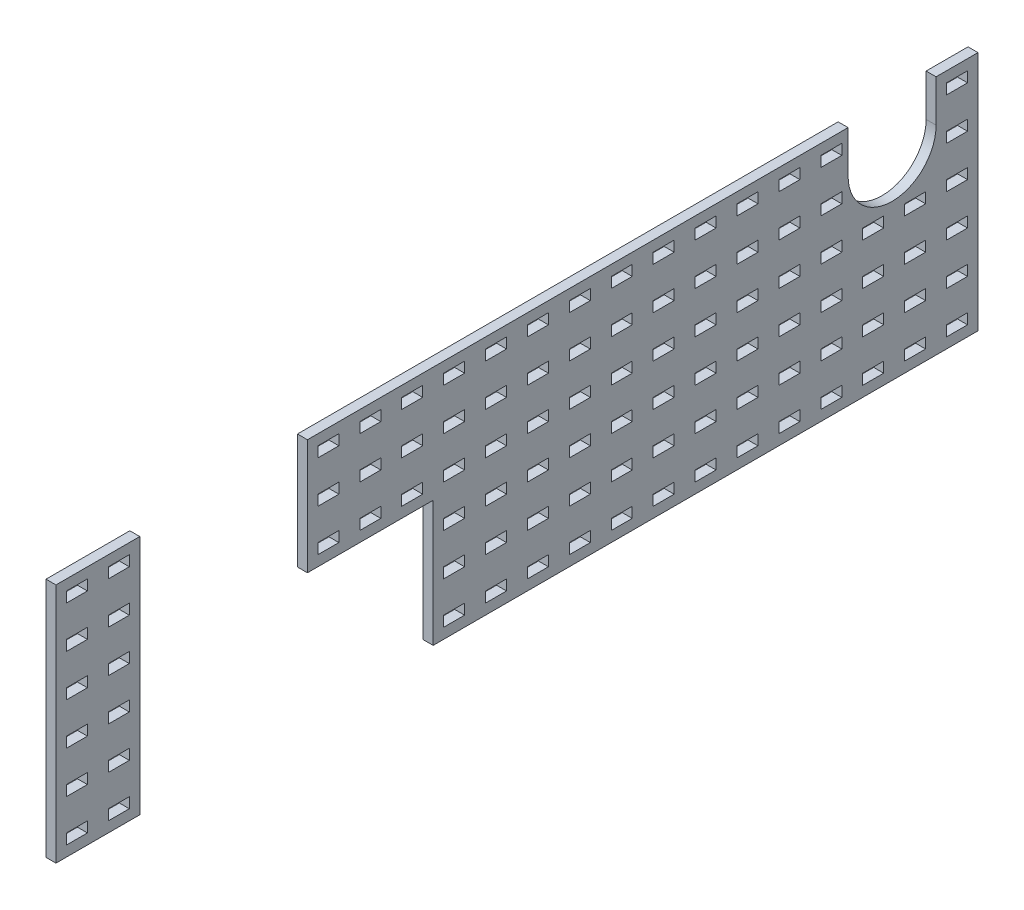
SolidWorks part; units mm, degrees
ref_plane "Front Plane" through (0, 0, 0) normal (0, 0, 1) x (1, 0, 0)
ref_plane "Top Plane" through (0, 0, 0) normal (0, 1, 0) x (1, 0, 0)
ref_plane "Right Plane" through (0, 0, 0) normal (1, 0, 0) x (0, 0, -1)
sketch "Sketch1" plane through (0, 0, 0) normal (1, 0, 0) x (0, 0, -1)
  line L1 (-279.4, -73.025) -> (279.4, -73.025)
  line L2 (-279.4, -73.025) -> (-279.4, 73.025)
  line L3 (-279.4, 73.025) -> (279.4, 73.025)
  line L4 (279.4, -73.025) -> (279.4, 73.025)
  line L5 (-279.4, -73.025) -> (279.4, 73.025) construction
  line L6 (-279.4, 73.025) -> (279.4, -73.025) construction
  point P0 (0, 0)
  dimension "D1" = 558.8
  dimension "D2" = 146.05
extrude "Boss-Extrude1" add sketch "Sketch1" along normal mid plane 6.0452
sketch "Sketch2" plane through (3.0226, 0, 0) normal (1, 0, 0) x (0, 0, -1)
  line L0 (-279.4, -73.025) -> (279.4, -73.025) construction
  line L1 (260.35, -60.325) -> (273.05, -60.325)
  line L2 (260.35, -60.325) -> (260.35, -66.675)
  line L3 (260.35, -66.675) -> (273.05, -66.675)
  line L4 (273.05, -60.325) -> (273.05, -66.675)
  line L5 (260.35, -60.325) -> (273.05, -66.675) construction
  line L6 (260.35, -66.675) -> (273.05, -60.325) construction
  line L7 (279.4, -73.025) -> (279.4, 73.025) construction
  line L8 (234.95, -66.675) -> (247.65, -66.675)
  line L9 (234.95, -60.325) -> (234.95, -66.675)
  line L10 (234.95, -60.325) -> (247.65, -60.325)
  line L11 (247.65, -60.325) -> (247.65, -66.675)
  line L12 (209.55, -66.675) -> (222.25, -66.675)
  line L13 (209.55, -60.325) -> (209.55, -66.675)
  line L14 (209.55, -60.325) -> (222.25, -60.325)
  line L15 (222.25, -60.325) -> (222.25, -66.675)
  line L16 (184.15, -66.675) -> (196.85, -66.675)
  line L17 (184.15, -60.325) -> (184.15, -66.675)
  line L18 (184.15, -60.325) -> (196.85, -60.325)
  line L19 (196.85, -60.325) -> (196.85, -66.675)
  line L20 (158.75, -66.675) -> (171.45, -66.675)
  line L21 (158.75, -60.325) -> (158.75, -66.675)
  line L22 (158.75, -60.325) -> (171.45, -60.325)
  line L23 (171.45, -60.325) -> (171.45, -66.675)
  line L24 (133.35, -66.675) -> (146.05, -66.675)
  line L25 (133.35, -60.325) -> (133.35, -66.675)
  line L26 (133.35, -60.325) -> (146.05, -60.325)
  line L27 (146.05, -60.325) -> (146.05, -66.675)
  line L28 (107.95, -66.675) -> (120.65, -66.675)
  line L29 (107.95, -60.325) -> (107.95, -66.675)
  line L30 (107.95, -60.325) -> (120.65, -60.325)
  line L31 (120.65, -60.325) -> (120.65, -66.675)
  line L32 (82.55, -66.675) -> (95.25, -66.675)
  line L33 (82.55, -60.325) -> (82.55, -66.675)
  line L34 (82.55, -60.325) -> (95.25, -60.325)
  line L35 (95.25, -60.325) -> (95.25, -66.675)
  line L36 (57.15, -66.675) -> (69.85, -66.675)
  line L37 (57.15, -60.325) -> (57.15, -66.675)
  line L38 (57.15, -60.325) -> (69.85, -60.325)
  line L39 (69.85, -60.325) -> (69.85, -66.675)
  line L40 (31.75, -66.675) -> (44.45, -66.675)
  line L41 (31.75, -60.325) -> (31.75, -66.675)
  line L42 (31.75, -60.325) -> (44.45, -60.325)
  line L43 (44.45, -60.325) -> (44.45, -66.675)
  line L44 (6.35, -66.675) -> (19.05, -66.675)
  line L45 (6.35, -60.325) -> (6.35, -66.675)
  line L46 (6.35, -60.325) -> (19.05, -60.325)
  line L47 (19.05, -60.325) -> (19.05, -66.675)
  line L48 (-19.05, -66.675) -> (-6.35, -66.675)
  line L49 (-19.05, -60.325) -> (-19.05, -66.675)
  line L50 (-19.05, -60.325) -> (-6.35, -60.325)
  line L51 (-6.35, -60.325) -> (-6.35, -66.675)
  line L52 (-44.45, -66.675) -> (-31.75, -66.675)
  line L53 (-44.45, -60.325) -> (-44.45, -66.675)
  line L54 (-44.45, -60.325) -> (-31.75, -60.325)
  line L55 (-31.75, -60.325) -> (-31.75, -66.675)
  line L56 (-69.85, -66.675) -> (-57.15, -66.675)
  line L57 (-69.85, -60.325) -> (-69.85, -66.675)
  line L58 (-69.85, -60.325) -> (-57.15, -60.325)
  line L59 (-57.15, -60.325) -> (-57.15, -66.675)
  line L60 (-95.25, -66.675) -> (-82.55, -66.675)
  line L61 (-95.25, -60.325) -> (-95.25, -66.675)
  line L62 (-95.25, -60.325) -> (-82.55, -60.325)
  line L63 (-82.55, -60.325) -> (-82.55, -66.675)
  line L64 (-120.65, -66.675) -> (-107.95, -66.675)
  line L65 (-120.65, -60.325) -> (-120.65, -66.675)
  line L66 (-120.65, -60.325) -> (-107.95, -60.325)
  line L67 (-107.95, -60.325) -> (-107.95, -66.675)
  line L68 (-146.05, -66.675) -> (-133.35, -66.675)
  line L69 (-146.05, -60.325) -> (-146.05, -66.675)
  line L70 (-146.05, -60.325) -> (-133.35, -60.325)
  line L71 (-133.35, -60.325) -> (-133.35, -66.675)
  line L72 (-171.45, -66.675) -> (-158.75, -66.675)
  line L73 (-171.45, -60.325) -> (-171.45, -66.675)
  line L74 (-171.45, -60.325) -> (-158.75, -60.325)
  line L75 (-158.75, -60.325) -> (-158.75, -66.675)
  line L76 (-196.85, -66.675) -> (-184.15, -66.675)
  line L77 (-196.85, -60.325) -> (-196.85, -66.675)
  line L78 (-196.85, -60.325) -> (-184.15, -60.325)
  line L79 (-184.15, -60.325) -> (-184.15, -66.675)
  line L80 (-222.25, -66.675) -> (-209.55, -66.675)
  line L81 (-222.25, -60.325) -> (-222.25, -66.675)
  line L82 (-222.25, -60.325) -> (-209.55, -60.325)
  line L83 (-209.55, -60.325) -> (-209.55, -66.675)
  line L84 (-247.65, -66.675) -> (-234.95, -66.675)
  line L85 (-247.65, -60.325) -> (-247.65, -66.675)
  line L86 (-247.65, -60.325) -> (-234.95, -60.325)
  line L87 (-234.95, -60.325) -> (-234.95, -66.675)
  line L88 (-273.05, -66.675) -> (-260.35, -66.675)
  line L89 (-273.05, -60.325) -> (-273.05, -66.675)
  line L90 (-273.05, -60.325) -> (-260.35, -60.325)
  line L91 (-260.35, -60.325) -> (-260.35, -66.675)
  line L92 (234.95, -41.275) -> (247.65, -41.275)
  line L93 (234.95, -34.925) -> (234.95, -41.275)
  line L94 (234.95, -34.925) -> (247.65, -34.925)
  line L95 (247.65, -34.925) -> (247.65, -41.275)
  line L96 (209.55, -41.275) -> (222.25, -41.275)
  line L97 (209.55, -34.925) -> (209.55, -41.275)
  line L98 (209.55, -34.925) -> (222.25, -34.925)
  line L99 (222.25, -34.925) -> (222.25, -41.275)
  line L100 (184.15, -41.275) -> (196.85, -41.275)
  line L101 (184.15, -34.925) -> (184.15, -41.275)
  line L102 (184.15, -34.925) -> (196.85, -34.925)
  line L103 (196.85, -34.925) -> (196.85, -41.275)
  line L104 (158.75, -41.275) -> (171.45, -41.275)
  line L105 (158.75, -34.925) -> (158.75, -41.275)
  line L106 (158.75, -34.925) -> (171.45, -34.925)
  line L107 (171.45, -34.925) -> (171.45, -41.275)
  line L108 (133.35, -41.275) -> (146.05, -41.275)
  line L109 (133.35, -34.925) -> (133.35, -41.275)
  line L110 (133.35, -34.925) -> (146.05, -34.925)
  line L111 (146.05, -34.925) -> (146.05, -41.275)
  line L112 (107.95, -41.275) -> (120.65, -41.275)
  line L113 (107.95, -34.925) -> (107.95, -41.275)
  line L114 (107.95, -34.925) -> (120.65, -34.925)
  line L115 (120.65, -34.925) -> (120.65, -41.275)
  line L116 (82.55, -41.275) -> (95.25, -41.275)
  line L117 (82.55, -34.925) -> (82.55, -41.275)
  line L118 (82.55, -34.925) -> (95.25, -34.925)
  line L119 (95.25, -34.925) -> (95.25, -41.275)
  line L120 (57.15, -41.275) -> (69.85, -41.275)
  line L121 (57.15, -34.925) -> (57.15, -41.275)
  line L122 (57.15, -34.925) -> (69.85, -34.925)
  line L123 (69.85, -34.925) -> (69.85, -41.275)
  line L124 (31.75, -41.275) -> (44.45, -41.275)
  line L125 (31.75, -34.925) -> (31.75, -41.275)
  line L126 (31.75, -34.925) -> (44.45, -34.925)
  line L127 (44.45, -34.925) -> (44.45, -41.275)
  line L128 (6.35, -41.275) -> (19.05, -41.275)
  line L129 (6.35, -34.925) -> (6.35, -41.275)
  line L130 (6.35, -34.925) -> (19.05, -34.925)
  line L131 (19.05, -34.925) -> (19.05, -41.275)
  line L132 (-19.05, -41.275) -> (-6.35, -41.275)
  line L133 (-19.05, -34.925) -> (-19.05, -41.275)
  line L134 (-19.05, -34.925) -> (-6.35, -34.925)
  line L135 (-6.35, -34.925) -> (-6.35, -41.275)
  line L136 (-44.45, -41.275) -> (-31.75, -41.275)
  line L137 (-44.45, -34.925) -> (-44.45, -41.275)
  line L138 (-44.45, -34.925) -> (-31.75, -34.925)
  line L139 (-31.75, -34.925) -> (-31.75, -41.275)
  line L140 (-69.85, -41.275) -> (-57.15, -41.275)
  line L141 (-69.85, -34.925) -> (-69.85, -41.275)
  line L142 (-69.85, -34.925) -> (-57.15, -34.925)
  line L143 (-57.15, -34.925) -> (-57.15, -41.275)
  line L144 (-95.25, -41.275) -> (-82.55, -41.275)
  line L145 (-95.25, -34.925) -> (-95.25, -41.275)
  line L146 (-95.25, -34.925) -> (-82.55, -34.925)
  line L147 (-82.55, -34.925) -> (-82.55, -41.275)
  line L148 (-120.65, -41.275) -> (-107.95, -41.275)
  line L149 (-120.65, -34.925) -> (-120.65, -41.275)
  line L150 (-120.65, -34.925) -> (-107.95, -34.925)
  line L151 (-107.95, -34.925) -> (-107.95, -41.275)
  line L152 (-146.05, -41.275) -> (-133.35, -41.275)
  line L153 (-146.05, -34.925) -> (-146.05, -41.275)
  line L154 (-146.05, -34.925) -> (-133.35, -34.925)
  line L155 (-133.35, -34.925) -> (-133.35, -41.275)
  line L156 (-171.45, -41.275) -> (-158.75, -41.275)
  line L157 (-171.45, -34.925) -> (-171.45, -41.275)
  line L158 (-171.45, -34.925) -> (-158.75, -34.925)
  line L159 (-158.75, -34.925) -> (-158.75, -41.275)
  line L160 (-196.85, -41.275) -> (-184.15, -41.275)
  line L161 (-196.85, -34.925) -> (-196.85, -41.275)
  line L162 (-196.85, -34.925) -> (-184.15, -34.925)
  line L163 (-184.15, -34.925) -> (-184.15, -41.275)
  line L164 (-222.25, -41.275) -> (-209.55, -41.275)
  line L165 (-222.25, -34.925) -> (-222.25, -41.275)
  line L166 (-222.25, -34.925) -> (-209.55, -34.925)
  line L167 (-209.55, -34.925) -> (-209.55, -41.275)
  line L168 (-247.65, -41.275) -> (-234.95, -41.275)
  line L169 (-247.65, -34.925) -> (-247.65, -41.275)
  line L170 (-247.65, -34.925) -> (-234.95, -34.925)
  line L171 (-234.95, -34.925) -> (-234.95, -41.275)
  line L172 (-273.05, -41.275) -> (-260.35, -41.275)
  line L173 (-273.05, -34.925) -> (-273.05, -41.275)
  line L174 (-273.05, -34.925) -> (-260.35, -34.925)
  line L175 (-260.35, -34.925) -> (-260.35, -41.275)
  line L176 (234.95, -15.875) -> (247.65, -15.875)
  line L177 (234.95, -9.525) -> (234.95, -15.875)
  line L178 (234.95, -9.525) -> (247.65, -9.525)
  line L179 (247.65, -9.525) -> (247.65, -15.875)
  line L180 (209.55, -15.875) -> (222.25, -15.875)
  line L181 (209.55, -9.525) -> (209.55, -15.875)
  line L182 (209.55, -9.525) -> (222.25, -9.525)
  line L183 (222.25, -9.525) -> (222.25, -15.875)
  line L184 (184.15, -15.875) -> (196.85, -15.875)
  line L185 (184.15, -9.525) -> (184.15, -15.875)
  line L186 (184.15, -9.525) -> (196.85, -9.525)
  line L187 (196.85, -9.525) -> (196.85, -15.875)
  line L188 (158.75, -15.875) -> (171.45, -15.875)
  line L189 (158.75, -9.525) -> (158.75, -15.875)
  line L190 (158.75, -9.525) -> (171.45, -9.525)
  line L191 (171.45, -9.525) -> (171.45, -15.875)
  line L192 (133.35, -15.875) -> (146.05, -15.875)
  line L193 (133.35, -9.525) -> (133.35, -15.875)
  line L194 (133.35, -9.525) -> (146.05, -9.525)
  line L195 (146.05, -9.525) -> (146.05, -15.875)
  line L196 (107.95, -15.875) -> (120.65, -15.875)
  line L197 (107.95, -9.525) -> (107.95, -15.875)
  line L198 (107.95, -9.525) -> (120.65, -9.525)
  line L199 (120.65, -9.525) -> (120.65, -15.875)
  line L200 (82.55, -15.875) -> (95.25, -15.875)
  line L201 (82.55, -9.525) -> (82.55, -15.875)
  line L202 (82.55, -9.525) -> (95.25, -9.525)
  line L203 (95.25, -9.525) -> (95.25, -15.875)
  line L204 (57.15, -15.875) -> (69.85, -15.875)
  line L205 (57.15, -9.525) -> (57.15, -15.875)
  line L206 (57.15, -9.525) -> (69.85, -9.525)
  line L207 (69.85, -9.525) -> (69.85, -15.875)
  line L208 (31.75, -15.875) -> (44.45, -15.875)
  line L209 (31.75, -9.525) -> (31.75, -15.875)
  line L210 (31.75, -9.525) -> (44.45, -9.525)
  line L211 (44.45, -9.525) -> (44.45, -15.875)
  line L212 (6.35, -15.875) -> (19.05, -15.875)
  line L213 (6.35, -9.525) -> (6.35, -15.875)
  line L214 (6.35, -9.525) -> (19.05, -9.525)
  line L215 (19.05, -9.525) -> (19.05, -15.875)
  line L216 (-19.05, -15.875) -> (-6.35, -15.875)
  line L217 (-19.05, -9.525) -> (-19.05, -15.875)
  line L218 (-19.05, -9.525) -> (-6.35, -9.525)
  line L219 (-6.35, -9.525) -> (-6.35, -15.875)
  line L220 (-44.45, -15.875) -> (-31.75, -15.875)
  line L221 (-44.45, -9.525) -> (-44.45, -15.875)
  line L222 (-44.45, -9.525) -> (-31.75, -9.525)
  line L223 (-31.75, -9.525) -> (-31.75, -15.875)
  line L224 (-69.85, -15.875) -> (-57.15, -15.875)
  line L225 (-69.85, -9.525) -> (-69.85, -15.875)
  line L226 (-69.85, -9.525) -> (-57.15, -9.525)
  line L227 (-57.15, -9.525) -> (-57.15, -15.875)
  line L228 (-95.25, -15.875) -> (-82.55, -15.875)
  line L229 (-95.25, -9.525) -> (-95.25, -15.875)
  line L230 (-95.25, -9.525) -> (-82.55, -9.525)
  line L231 (-82.55, -9.525) -> (-82.55, -15.875)
  line L232 (-120.65, -15.875) -> (-107.95, -15.875)
  line L233 (-120.65, -9.525) -> (-120.65, -15.875)
  line L234 (-120.65, -9.525) -> (-107.95, -9.525)
  line L235 (-107.95, -9.525) -> (-107.95, -15.875)
  line L236 (-146.05, -15.875) -> (-133.35, -15.875)
  line L237 (-146.05, -9.525) -> (-146.05, -15.875)
  line L238 (-146.05, -9.525) -> (-133.35, -9.525)
  line L239 (-133.35, -9.525) -> (-133.35, -15.875)
  line L240 (-171.45, -15.875) -> (-158.75, -15.875)
  line L241 (-171.45, -9.525) -> (-171.45, -15.875)
  line L242 (-171.45, -9.525) -> (-158.75, -9.525)
  line L243 (-158.75, -9.525) -> (-158.75, -15.875)
  line L244 (-196.85, -15.875) -> (-184.15, -15.875)
  line L245 (-196.85, -9.525) -> (-196.85, -15.875)
  line L246 (-196.85, -9.525) -> (-184.15, -9.525)
  line L247 (-184.15, -9.525) -> (-184.15, -15.875)
  line L248 (-222.25, -15.875) -> (-209.55, -15.875)
  line L249 (-222.25, -9.525) -> (-222.25, -15.875)
  line L250 (-222.25, -9.525) -> (-209.55, -9.525)
  line L251 (-209.55, -9.525) -> (-209.55, -15.875)
  line L252 (-247.65, -15.875) -> (-234.95, -15.875)
  line L253 (-247.65, -9.525) -> (-247.65, -15.875)
  line L254 (-247.65, -9.525) -> (-234.95, -9.525)
  line L255 (-234.95, -9.525) -> (-234.95, -15.875)
  line L256 (-273.05, -15.875) -> (-260.35, -15.875)
  line L257 (-273.05, -9.525) -> (-273.05, -15.875)
  line L258 (-273.05, -9.525) -> (-260.35, -9.525)
  line L259 (-260.35, -9.525) -> (-260.35, -15.875)
  line L260 (234.95, 9.525) -> (247.65, 9.525)
  line L261 (234.95, 15.875) -> (234.95, 9.525)
  line L262 (234.95, 15.875) -> (247.65, 15.875)
  line L263 (247.65, 15.875) -> (247.65, 9.525)
  line L264 (209.55, 9.525) -> (222.25, 9.525)
  line L265 (209.55, 15.875) -> (209.55, 9.525)
  line L266 (209.55, 15.875) -> (222.25, 15.875)
  line L267 (222.25, 15.875) -> (222.25, 9.525)
  line L268 (184.15, 9.525) -> (196.85, 9.525)
  line L269 (184.15, 15.875) -> (184.15, 9.525)
  line L270 (184.15, 15.875) -> (196.85, 15.875)
  line L271 (196.85, 15.875) -> (196.85, 9.525)
  line L272 (158.75, 9.525) -> (171.45, 9.525)
  line L273 (158.75, 15.875) -> (158.75, 9.525)
  line L274 (158.75, 15.875) -> (171.45, 15.875)
  line L275 (171.45, 15.875) -> (171.45, 9.525)
  line L276 (133.35, 9.525) -> (146.05, 9.525)
  line L277 (133.35, 15.875) -> (133.35, 9.525)
  line L278 (133.35, 15.875) -> (146.05, 15.875)
  line L279 (146.05, 15.875) -> (146.05, 9.525)
  line L280 (107.95, 9.525) -> (120.65, 9.525)
  line L281 (107.95, 15.875) -> (107.95, 9.525)
  line L282 (107.95, 15.875) -> (120.65, 15.875)
  line L283 (120.65, 15.875) -> (120.65, 9.525)
  line L284 (82.55, 9.525) -> (95.25, 9.525)
  line L285 (82.55, 15.875) -> (82.55, 9.525)
  line L286 (82.55, 15.875) -> (95.25, 15.875)
  line L287 (95.25, 15.875) -> (95.25, 9.525)
  line L288 (57.15, 9.525) -> (69.85, 9.525)
  line L289 (57.15, 15.875) -> (57.15, 9.525)
  line L290 (57.15, 15.875) -> (69.85, 15.875)
  line L291 (69.85, 15.875) -> (69.85, 9.525)
  line L292 (31.75, 9.525) -> (44.45, 9.525)
  line L293 (31.75, 15.875) -> (31.75, 9.525)
  line L294 (31.75, 15.875) -> (44.45, 15.875)
  line L295 (44.45, 15.875) -> (44.45, 9.525)
  line L296 (6.35, 9.525) -> (19.05, 9.525)
  line L297 (6.35, 15.875) -> (6.35, 9.525)
  line L298 (6.35, 15.875) -> (19.05, 15.875)
  line L299 (19.05, 15.875) -> (19.05, 9.525)
  line L300 (-19.05, 9.525) -> (-6.35, 9.525)
  line L301 (-19.05, 15.875) -> (-19.05, 9.525)
  line L302 (-19.05, 15.875) -> (-6.35, 15.875)
  line L303 (-6.35, 15.875) -> (-6.35, 9.525)
  line L304 (-44.45, 9.525) -> (-31.75, 9.525)
  line L305 (-44.45, 15.875) -> (-44.45, 9.525)
  line L306 (-44.45, 15.875) -> (-31.75, 15.875)
  line L307 (-31.75, 15.875) -> (-31.75, 9.525)
  line L308 (-69.85, 9.525) -> (-57.15, 9.525)
  line L309 (-69.85, 15.875) -> (-69.85, 9.525)
  line L310 (-69.85, 15.875) -> (-57.15, 15.875)
  line L311 (-57.15, 15.875) -> (-57.15, 9.525)
  line L312 (-95.25, 9.525) -> (-82.55, 9.525)
  line L313 (-95.25, 15.875) -> (-95.25, 9.525)
  line L314 (-95.25, 15.875) -> (-82.55, 15.875)
  line L315 (-82.55, 15.875) -> (-82.55, 9.525)
  line L316 (-120.65, 9.525) -> (-107.95, 9.525)
  line L317 (-120.65, 15.875) -> (-120.65, 9.525)
  line L318 (-120.65, 15.875) -> (-107.95, 15.875)
  line L319 (-107.95, 15.875) -> (-107.95, 9.525)
  line L320 (-146.05, 9.525) -> (-133.35, 9.525)
  line L321 (-146.05, 15.875) -> (-146.05, 9.525)
  line L322 (-146.05, 15.875) -> (-133.35, 15.875)
  line L323 (-133.35, 15.875) -> (-133.35, 9.525)
  line L324 (-171.45, 9.525) -> (-158.75, 9.525)
  line L325 (-171.45, 15.875) -> (-171.45, 9.525)
  line L326 (-171.45, 15.875) -> (-158.75, 15.875)
  line L327 (-158.75, 15.875) -> (-158.75, 9.525)
  line L328 (-196.85, 9.525) -> (-184.15, 9.525)
  line L329 (-196.85, 15.875) -> (-196.85, 9.525)
  line L330 (-196.85, 15.875) -> (-184.15, 15.875)
  line L331 (-184.15, 15.875) -> (-184.15, 9.525)
  line L332 (-222.25, 9.525) -> (-209.55, 9.525)
  line L333 (-222.25, 15.875) -> (-222.25, 9.525)
  line L334 (-222.25, 15.875) -> (-209.55, 15.875)
  line L335 (-209.55, 15.875) -> (-209.55, 9.525)
  line L336 (-247.65, 9.525) -> (-234.95, 9.525)
  line L337 (-247.65, 15.875) -> (-247.65, 9.525)
  line L338 (-247.65, 15.875) -> (-234.95, 15.875)
  line L339 (-234.95, 15.875) -> (-234.95, 9.525)
  line L340 (-273.05, 9.525) -> (-260.35, 9.525)
  line L341 (-273.05, 15.875) -> (-273.05, 9.525)
  line L342 (-273.05, 15.875) -> (-260.35, 15.875)
  line L343 (-260.35, 15.875) -> (-260.35, 9.525)
  line L344 (234.95, 34.925) -> (247.65, 34.925)
  line L345 (234.95, 41.275) -> (234.95, 34.925)
  line L346 (234.95, 41.275) -> (247.65, 41.275)
  line L347 (247.65, 41.275) -> (247.65, 34.925)
  line L348 (209.55, 34.925) -> (222.25, 34.925)
  line L349 (209.55, 41.275) -> (209.55, 34.925)
  line L350 (209.55, 41.275) -> (222.25, 41.275)
  line L351 (222.25, 41.275) -> (222.25, 34.925)
  line L352 (184.15, 34.925) -> (196.85, 34.925)
  line L353 (184.15, 41.275) -> (184.15, 34.925)
  line L354 (184.15, 41.275) -> (196.85, 41.275)
  line L355 (196.85, 41.275) -> (196.85, 34.925)
  line L356 (158.75, 34.925) -> (171.45, 34.925)
  line L357 (158.75, 41.275) -> (158.75, 34.925)
  line L358 (158.75, 41.275) -> (171.45, 41.275)
  line L359 (171.45, 41.275) -> (171.45, 34.925)
  line L360 (133.35, 34.925) -> (146.05, 34.925)
  line L361 (133.35, 41.275) -> (133.35, 34.925)
  line L362 (133.35, 41.275) -> (146.05, 41.275)
  line L363 (146.05, 41.275) -> (146.05, 34.925)
  line L364 (107.95, 34.925) -> (120.65, 34.925)
  line L365 (107.95, 41.275) -> (107.95, 34.925)
  line L366 (107.95, 41.275) -> (120.65, 41.275)
  line L367 (120.65, 41.275) -> (120.65, 34.925)
  line L368 (82.55, 34.925) -> (95.25, 34.925)
  line L369 (82.55, 41.275) -> (82.55, 34.925)
  line L370 (82.55, 41.275) -> (95.25, 41.275)
  line L371 (95.25, 41.275) -> (95.25, 34.925)
  line L372 (57.15, 34.925) -> (69.85, 34.925)
  line L373 (57.15, 41.275) -> (57.15, 34.925)
  line L374 (57.15, 41.275) -> (69.85, 41.275)
  line L375 (69.85, 41.275) -> (69.85, 34.925)
  line L376 (31.75, 34.925) -> (44.45, 34.925)
  line L377 (31.75, 41.275) -> (31.75, 34.925)
  line L378 (31.75, 41.275) -> (44.45, 41.275)
  line L379 (44.45, 41.275) -> (44.45, 34.925)
  line L380 (6.35, 34.925) -> (19.05, 34.925)
  line L381 (6.35, 41.275) -> (6.35, 34.925)
  line L382 (6.35, 41.275) -> (19.05, 41.275)
  line L383 (19.05, 41.275) -> (19.05, 34.925)
  line L384 (-19.05, 34.925) -> (-6.35, 34.925)
  line L385 (-19.05, 41.275) -> (-19.05, 34.925)
  line L386 (-19.05, 41.275) -> (-6.35, 41.275)
  line L387 (-6.35, 41.275) -> (-6.35, 34.925)
  line L388 (-44.45, 34.925) -> (-31.75, 34.925)
  line L389 (-44.45, 41.275) -> (-44.45, 34.925)
  line L390 (-44.45, 41.275) -> (-31.75, 41.275)
  line L391 (-31.75, 41.275) -> (-31.75, 34.925)
  line L392 (-69.85, 34.925) -> (-57.15, 34.925)
  line L393 (-69.85, 41.275) -> (-69.85, 34.925)
  line L394 (-69.85, 41.275) -> (-57.15, 41.275)
  line L395 (-57.15, 41.275) -> (-57.15, 34.925)
  line L396 (-95.25, 34.925) -> (-82.55, 34.925)
  line L397 (-95.25, 41.275) -> (-95.25, 34.925)
  line L398 (-95.25, 41.275) -> (-82.55, 41.275)
  line L399 (-82.55, 41.275) -> (-82.55, 34.925)
  line L400 (-120.65, 34.925) -> (-107.95, 34.925)
  line L401 (-120.65, 41.275) -> (-120.65, 34.925)
  line L402 (-120.65, 41.275) -> (-107.95, 41.275)
  line L403 (-107.95, 41.275) -> (-107.95, 34.925)
  line L404 (-146.05, 34.925) -> (-133.35, 34.925)
  line L405 (-146.05, 41.275) -> (-146.05, 34.925)
  line L406 (-146.05, 41.275) -> (-133.35, 41.275)
  line L407 (-133.35, 41.275) -> (-133.35, 34.925)
  line L408 (-171.45, 34.925) -> (-158.75, 34.925)
  line L409 (-171.45, 41.275) -> (-171.45, 34.925)
  line L410 (-171.45, 41.275) -> (-158.75, 41.275)
  line L411 (-158.75, 41.275) -> (-158.75, 34.925)
  line L412 (-196.85, 34.925) -> (-184.15, 34.925)
  line L413 (-196.85, 41.275) -> (-196.85, 34.925)
  line L414 (-196.85, 41.275) -> (-184.15, 41.275)
  line L415 (-184.15, 41.275) -> (-184.15, 34.925)
  line L416 (-222.25, 34.925) -> (-209.55, 34.925)
  line L417 (-222.25, 41.275) -> (-222.25, 34.925)
  line L418 (-222.25, 41.275) -> (-209.55, 41.275)
  line L419 (-209.55, 41.275) -> (-209.55, 34.925)
  line L420 (-247.65, 34.925) -> (-234.95, 34.925)
  line L421 (-247.65, 41.275) -> (-247.65, 34.925)
  line L422 (-247.65, 41.275) -> (-234.95, 41.275)
  line L423 (-234.95, 41.275) -> (-234.95, 34.925)
  line L424 (-273.05, 34.925) -> (-260.35, 34.925)
  line L425 (-273.05, 41.275) -> (-273.05, 34.925)
  line L426 (-273.05, 41.275) -> (-260.35, 41.275)
  line L427 (-260.35, 41.275) -> (-260.35, 34.925)
  line L428 (234.95, 60.325) -> (247.65, 60.325)
  line L429 (234.95, 66.675) -> (234.95, 60.325)
  line L430 (234.95, 66.675) -> (247.65, 66.675)
  line L431 (247.65, 66.675) -> (247.65, 60.325)
  line L432 (209.55, 60.325) -> (222.25, 60.325)
  line L433 (209.55, 66.675) -> (209.55, 60.325)
  line L434 (209.55, 66.675) -> (222.25, 66.675)
  line L435 (222.25, 66.675) -> (222.25, 60.325)
  line L436 (184.15, 60.325) -> (196.85, 60.325)
  line L437 (184.15, 66.675) -> (184.15, 60.325)
  line L438 (184.15, 66.675) -> (196.85, 66.675)
  line L439 (196.85, 66.675) -> (196.85, 60.325)
  line L440 (158.75, 60.325) -> (171.45, 60.325)
  line L441 (158.75, 66.675) -> (158.75, 60.325)
  line L442 (158.75, 66.675) -> (171.45, 66.675)
  line L443 (171.45, 66.675) -> (171.45, 60.325)
  line L444 (133.35, 60.325) -> (146.05, 60.325)
  line L445 (133.35, 66.675) -> (133.35, 60.325)
  line L446 (133.35, 66.675) -> (146.05, 66.675)
  line L447 (146.05, 66.675) -> (146.05, 60.325)
  line L448 (107.95, 60.325) -> (120.65, 60.325)
  line L449 (107.95, 66.675) -> (107.95, 60.325)
  line L450 (107.95, 66.675) -> (120.65, 66.675)
  line L451 (120.65, 66.675) -> (120.65, 60.325)
  line L452 (82.55, 60.325) -> (95.25, 60.325)
  line L453 (82.55, 66.675) -> (82.55, 60.325)
  line L454 (82.55, 66.675) -> (95.25, 66.675)
  line L455 (95.25, 66.675) -> (95.25, 60.325)
  line L456 (57.15, 60.325) -> (69.85, 60.325)
  line L457 (57.15, 66.675) -> (57.15, 60.325)
  line L458 (57.15, 66.675) -> (69.85, 66.675)
  line L459 (69.85, 66.675) -> (69.85, 60.325)
  line L460 (31.75, 60.325) -> (44.45, 60.325)
  line L461 (31.75, 66.675) -> (31.75, 60.325)
  line L462 (31.75, 66.675) -> (44.45, 66.675)
  line L463 (44.45, 66.675) -> (44.45, 60.325)
  line L464 (6.35, 60.325) -> (19.05, 60.325)
  line L465 (6.35, 66.675) -> (6.35, 60.325)
  line L466 (6.35, 66.675) -> (19.05, 66.675)
  line L467 (19.05, 66.675) -> (19.05, 60.325)
  line L468 (-19.05, 60.325) -> (-6.35, 60.325)
  line L469 (-19.05, 66.675) -> (-19.05, 60.325)
  line L470 (-19.05, 66.675) -> (-6.35, 66.675)
  line L471 (-6.35, 66.675) -> (-6.35, 60.325)
  line L472 (-44.45, 60.325) -> (-31.75, 60.325)
  line L473 (-44.45, 66.675) -> (-44.45, 60.325)
  line L474 (-44.45, 66.675) -> (-31.75, 66.675)
  line L475 (-31.75, 66.675) -> (-31.75, 60.325)
  line L476 (-69.85, 60.325) -> (-57.15, 60.325)
  line L477 (-69.85, 66.675) -> (-69.85, 60.325)
  line L478 (-69.85, 66.675) -> (-57.15, 66.675)
  line L479 (-57.15, 66.675) -> (-57.15, 60.325)
  line L480 (-95.25, 60.325) -> (-82.55, 60.325)
  line L481 (-95.25, 66.675) -> (-95.25, 60.325)
  line L482 (-95.25, 66.675) -> (-82.55, 66.675)
  line L483 (-82.55, 66.675) -> (-82.55, 60.325)
  line L484 (-120.65, 60.325) -> (-107.95, 60.325)
  line L485 (-120.65, 66.675) -> (-120.65, 60.325)
  line L486 (-120.65, 66.675) -> (-107.95, 66.675)
  line L487 (-107.95, 66.675) -> (-107.95, 60.325)
  line L488 (-146.05, 60.325) -> (-133.35, 60.325)
  line L489 (-146.05, 66.675) -> (-146.05, 60.325)
  line L490 (-146.05, 66.675) -> (-133.35, 66.675)
  line L491 (-133.35, 66.675) -> (-133.35, 60.325)
  line L492 (-171.45, 60.325) -> (-158.75, 60.325)
  line L493 (-171.45, 66.675) -> (-171.45, 60.325)
  line L494 (-171.45, 66.675) -> (-158.75, 66.675)
  line L495 (-158.75, 66.675) -> (-158.75, 60.325)
  line L496 (-196.85, 60.325) -> (-184.15, 60.325)
  line L497 (-196.85, 66.675) -> (-196.85, 60.325)
  line L498 (-196.85, 66.675) -> (-184.15, 66.675)
  line L499 (-184.15, 66.675) -> (-184.15, 60.325)
  line L500 (-222.25, 60.325) -> (-209.55, 60.325)
  line L501 (-222.25, 66.675) -> (-222.25, 60.325)
  line L502 (-222.25, 66.675) -> (-209.55, 66.675)
  line L503 (-209.55, 66.675) -> (-209.55, 60.325)
  line L504 (-247.65, 60.325) -> (-234.95, 60.325)
  line L505 (-247.65, 66.675) -> (-247.65, 60.325)
  line L506 (-247.65, 66.675) -> (-234.95, 66.675)
  line L507 (-234.95, 66.675) -> (-234.95, 60.325)
  line L508 (-273.05, 60.325) -> (-260.35, 60.325)
  line L509 (-273.05, 66.675) -> (-273.05, 60.325)
  line L510 (-273.05, 66.675) -> (-260.35, 66.675)
  line L511 (-260.35, 66.675) -> (-260.35, 60.325)
  line L512 (234.95, 85.725) -> (247.65, 85.725)
  line L513 (234.95, 92.075) -> (234.95, 85.725)
  line L514 (234.95, 92.075) -> (247.65, 92.075)
  line L515 (247.65, 92.075) -> (247.65, 85.725)
  line L516 (209.55, 85.725) -> (222.25, 85.725)
  line L517 (209.55, 92.075) -> (209.55, 85.725)
  line L518 (209.55, 92.075) -> (222.25, 92.075)
  line L519 (222.25, 92.075) -> (222.25, 85.725)
  line L520 (184.15, 85.725) -> (196.85, 85.725)
  line L521 (184.15, 92.075) -> (184.15, 85.725)
  line L522 (184.15, 92.075) -> (196.85, 92.075)
  line L523 (196.85, 92.075) -> (196.85, 85.725)
  line L524 (158.75, 85.725) -> (171.45, 85.725)
  line L525 (158.75, 92.075) -> (158.75, 85.725)
  line L526 (158.75, 92.075) -> (171.45, 92.075)
  line L527 (171.45, 92.075) -> (171.45, 85.725)
  line L528 (133.35, 85.725) -> (146.05, 85.725)
  line L529 (133.35, 92.075) -> (133.35, 85.725)
  line L530 (133.35, 92.075) -> (146.05, 92.075)
  line L531 (146.05, 92.075) -> (146.05, 85.725)
  line L532 (107.95, 85.725) -> (120.65, 85.725)
  line L533 (107.95, 92.075) -> (107.95, 85.725)
  line L534 (107.95, 92.075) -> (120.65, 92.075)
  line L535 (120.65, 92.075) -> (120.65, 85.725)
  line L536 (82.55, 85.725) -> (95.25, 85.725)
  line L537 (82.55, 92.075) -> (82.55, 85.725)
  line L538 (82.55, 92.075) -> (95.25, 92.075)
  line L539 (95.25, 92.075) -> (95.25, 85.725)
  line L540 (57.15, 85.725) -> (69.85, 85.725)
  line L541 (57.15, 92.075) -> (57.15, 85.725)
  line L542 (57.15, 92.075) -> (69.85, 92.075)
  line L543 (69.85, 92.075) -> (69.85, 85.725)
  line L544 (31.75, 85.725) -> (44.45, 85.725)
  line L545 (31.75, 92.075) -> (31.75, 85.725)
  line L546 (31.75, 92.075) -> (44.45, 92.075)
  line L547 (44.45, 92.075) -> (44.45, 85.725)
  line L548 (6.35, 85.725) -> (19.05, 85.725)
  line L549 (6.35, 92.075) -> (6.35, 85.725)
  line L550 (6.35, 92.075) -> (19.05, 92.075)
  line L551 (19.05, 92.075) -> (19.05, 85.725)
  line L552 (-19.05, 85.725) -> (-6.35, 85.725)
  line L553 (-19.05, 92.075) -> (-19.05, 85.725)
  line L554 (-19.05, 92.075) -> (-6.35, 92.075)
  line L555 (-6.35, 92.075) -> (-6.35, 85.725)
  line L556 (-44.45, 85.725) -> (-31.75, 85.725)
  line L557 (-44.45, 92.075) -> (-44.45, 85.725)
  line L558 (-44.45, 92.075) -> (-31.75, 92.075)
  line L559 (-31.75, 92.075) -> (-31.75, 85.725)
  line L560 (-69.85, 85.725) -> (-57.15, 85.725)
  line L561 (-69.85, 92.075) -> (-69.85, 85.725)
  line L562 (-69.85, 92.075) -> (-57.15, 92.075)
  line L563 (-57.15, 92.075) -> (-57.15, 85.725)
  line L564 (-95.25, 85.725) -> (-82.55, 85.725)
  line L565 (-95.25, 92.075) -> (-95.25, 85.725)
  line L566 (-95.25, 92.075) -> (-82.55, 92.075)
  line L567 (-82.55, 92.075) -> (-82.55, 85.725)
  line L568 (-120.65, 85.725) -> (-107.95, 85.725)
  line L569 (-120.65, 92.075) -> (-120.65, 85.725)
  line L570 (-120.65, 92.075) -> (-107.95, 92.075)
  line L571 (-107.95, 92.075) -> (-107.95, 85.725)
  line L572 (-146.05, 85.725) -> (-133.35, 85.725)
  line L573 (-146.05, 92.075) -> (-146.05, 85.725)
  line L574 (-146.05, 92.075) -> (-133.35, 92.075)
  line L575 (-133.35, 92.075) -> (-133.35, 85.725)
  line L576 (-171.45, 85.725) -> (-158.75, 85.725)
  line L577 (-171.45, 92.075) -> (-171.45, 85.725)
  line L578 (-171.45, 92.075) -> (-158.75, 92.075)
  line L579 (-158.75, 92.075) -> (-158.75, 85.725)
  line L580 (-196.85, 85.725) -> (-184.15, 85.725)
  line L581 (-196.85, 92.075) -> (-196.85, 85.725)
  line L582 (-196.85, 92.075) -> (-184.15, 92.075)
  line L583 (-184.15, 92.075) -> (-184.15, 85.725)
  line L584 (-222.25, 85.725) -> (-209.55, 85.725)
  line L585 (-222.25, 92.075) -> (-222.25, 85.725)
  line L586 (-222.25, 92.075) -> (-209.55, 92.075)
  line L587 (-209.55, 92.075) -> (-209.55, 85.725)
  line L588 (-247.65, 85.725) -> (-234.95, 85.725)
  line L589 (-247.65, 92.075) -> (-247.65, 85.725)
  line L590 (-247.65, 92.075) -> (-234.95, 92.075)
  line L591 (-234.95, 92.075) -> (-234.95, 85.725)
  line L592 (-273.05, 85.725) -> (-260.35, 85.725)
  line L593 (-273.05, 92.075) -> (-273.05, 85.725)
  line L594 (-273.05, 92.075) -> (-260.35, 92.075)
  line L595 (-260.35, 92.075) -> (-260.35, 85.725)
  line L596 (234.95, 111.125) -> (247.65, 111.125)
  line L597 (234.95, 117.475) -> (234.95, 111.125)
  line L598 (234.95, 117.475) -> (247.65, 117.475)
  line L599 (247.65, 117.475) -> (247.65, 111.125)
  line L600 (209.55, 111.125) -> (222.25, 111.125)
  line L601 (209.55, 117.475) -> (209.55, 111.125)
  line L602 (209.55, 117.475) -> (222.25, 117.475)
  line L603 (222.25, 117.475) -> (222.25, 111.125)
  line L604 (184.15, 111.125) -> (196.85, 111.125)
  line L605 (184.15, 117.475) -> (184.15, 111.125)
  line L606 (184.15, 117.475) -> (196.85, 117.475)
  line L607 (196.85, 117.475) -> (196.85, 111.125)
  line L608 (158.75, 111.125) -> (171.45, 111.125)
  line L609 (158.75, 117.475) -> (158.75, 111.125)
  line L610 (158.75, 117.475) -> (171.45, 117.475)
  line L611 (171.45, 117.475) -> (171.45, 111.125)
  line L612 (133.35, 111.125) -> (146.05, 111.125)
  line L613 (133.35, 117.475) -> (133.35, 111.125)
  line L614 (133.35, 117.475) -> (146.05, 117.475)
  line L615 (146.05, 117.475) -> (146.05, 111.125)
  line L616 (107.95, 111.125) -> (120.65, 111.125)
  line L617 (107.95, 117.475) -> (107.95, 111.125)
  line L618 (107.95, 117.475) -> (120.65, 117.475)
  line L619 (120.65, 117.475) -> (120.65, 111.125)
  line L620 (82.55, 111.125) -> (95.25, 111.125)
  line L621 (82.55, 117.475) -> (82.55, 111.125)
  line L622 (82.55, 117.475) -> (95.25, 117.475)
  line L623 (95.25, 117.475) -> (95.25, 111.125)
  line L624 (57.15, 111.125) -> (69.85, 111.125)
  line L625 (57.15, 117.475) -> (57.15, 111.125)
  line L626 (57.15, 117.475) -> (69.85, 117.475)
  line L627 (69.85, 117.475) -> (69.85, 111.125)
  line L628 (31.75, 111.125) -> (44.45, 111.125)
  line L629 (31.75, 117.475) -> (31.75, 111.125)
  line L630 (31.75, 117.475) -> (44.45, 117.475)
  line L631 (44.45, 117.475) -> (44.45, 111.125)
  line L632 (6.35, 111.125) -> (19.05, 111.125)
  line L633 (6.35, 117.475) -> (6.35, 111.125)
  line L634 (6.35, 117.475) -> (19.05, 117.475)
  line L635 (19.05, 117.475) -> (19.05, 111.125)
  line L636 (-19.05, 111.125) -> (-6.35, 111.125)
  line L637 (-19.05, 117.475) -> (-19.05, 111.125)
  line L638 (-19.05, 117.475) -> (-6.35, 117.475)
  line L639 (-6.35, 117.475) -> (-6.35, 111.125)
  line L640 (-44.45, 111.125) -> (-31.75, 111.125)
  line L641 (-44.45, 117.475) -> (-44.45, 111.125)
  line L642 (-44.45, 117.475) -> (-31.75, 117.475)
  line L643 (-31.75, 117.475) -> (-31.75, 111.125)
  line L644 (-69.85, 111.125) -> (-57.15, 111.125)
  line L645 (-69.85, 117.475) -> (-69.85, 111.125)
  line L646 (-69.85, 117.475) -> (-57.15, 117.475)
  line L647 (-57.15, 117.475) -> (-57.15, 111.125)
  line L648 (-95.25, 111.125) -> (-82.55, 111.125)
  line L649 (-95.25, 117.475) -> (-95.25, 111.125)
  line L650 (-95.25, 117.475) -> (-82.55, 117.475)
  line L651 (-82.55, 117.475) -> (-82.55, 111.125)
  line L652 (-120.65, 111.125) -> (-107.95, 111.125)
  line L653 (-120.65, 117.475) -> (-120.65, 111.125)
  line L654 (-120.65, 117.475) -> (-107.95, 117.475)
  line L655 (-107.95, 117.475) -> (-107.95, 111.125)
  line L656 (-146.05, 111.125) -> (-133.35, 111.125)
  line L657 (-146.05, 117.475) -> (-146.05, 111.125)
  line L658 (-146.05, 117.475) -> (-133.35, 117.475)
  line L659 (-133.35, 117.475) -> (-133.35, 111.125)
  line L660 (-171.45, 111.125) -> (-158.75, 111.125)
  line L661 (-171.45, 117.475) -> (-171.45, 111.125)
  line L662 (-171.45, 117.475) -> (-158.75, 117.475)
  line L663 (-158.75, 117.475) -> (-158.75, 111.125)
  line L664 (-196.85, 111.125) -> (-184.15, 111.125)
  line L665 (-196.85, 117.475) -> (-196.85, 111.125)
  line L666 (-196.85, 117.475) -> (-184.15, 117.475)
  line L667 (-184.15, 117.475) -> (-184.15, 111.125)
  line L668 (-222.25, 111.125) -> (-209.55, 111.125)
  line L669 (-222.25, 117.475) -> (-222.25, 111.125)
  line L670 (-222.25, 117.475) -> (-209.55, 117.475)
  line L671 (-209.55, 117.475) -> (-209.55, 111.125)
  line L672 (-247.65, 111.125) -> (-234.95, 111.125)
  line L673 (-247.65, 117.475) -> (-247.65, 111.125)
  line L674 (-247.65, 117.475) -> (-234.95, 117.475)
  line L675 (-234.95, 117.475) -> (-234.95, 111.125)
  line L676 (-273.05, 111.125) -> (-260.35, 111.125)
  line L677 (-273.05, 117.475) -> (-273.05, 111.125)
  line L678 (-273.05, 117.475) -> (-260.35, 117.475)
  line L679 (-260.35, 117.475) -> (-260.35, 111.125)
  line L680 (234.95, 136.525) -> (247.65, 136.525)
  line L681 (234.95, 142.875) -> (234.95, 136.525)
  line L682 (234.95, 142.875) -> (247.65, 142.875)
  line L683 (247.65, 142.875) -> (247.65, 136.525)
  line L684 (209.55, 136.525) -> (222.25, 136.525)
  line L685 (209.55, 142.875) -> (209.55, 136.525)
  line L686 (209.55, 142.875) -> (222.25, 142.875)
  line L687 (222.25, 142.875) -> (222.25, 136.525)
  line L688 (184.15, 136.525) -> (196.85, 136.525)
  line L689 (184.15, 142.875) -> (184.15, 136.525)
  line L690 (184.15, 142.875) -> (196.85, 142.875)
  line L691 (196.85, 142.875) -> (196.85, 136.525)
  line L692 (158.75, 136.525) -> (171.45, 136.525)
  line L693 (158.75, 142.875) -> (158.75, 136.525)
  line L694 (158.75, 142.875) -> (171.45, 142.875)
  line L695 (171.45, 142.875) -> (171.45, 136.525)
  line L696 (133.35, 136.525) -> (146.05, 136.525)
  line L697 (133.35, 142.875) -> (133.35, 136.525)
  line L698 (133.35, 142.875) -> (146.05, 142.875)
  line L699 (146.05, 142.875) -> (146.05, 136.525)
  line L700 (107.95, 136.525) -> (120.65, 136.525)
  line L701 (107.95, 142.875) -> (107.95, 136.525)
  line L702 (107.95, 142.875) -> (120.65, 142.875)
  line L703 (120.65, 142.875) -> (120.65, 136.525)
  line L704 (82.55, 136.525) -> (95.25, 136.525)
  line L705 (82.55, 142.875) -> (82.55, 136.525)
  line L706 (82.55, 142.875) -> (95.25, 142.875)
  line L707 (95.25, 142.875) -> (95.25, 136.525)
  line L708 (57.15, 136.525) -> (69.85, 136.525)
  line L709 (57.15, 142.875) -> (57.15, 136.525)
  line L710 (57.15, 142.875) -> (69.85, 142.875)
  line L711 (69.85, 142.875) -> (69.85, 136.525)
  line L712 (31.75, 136.525) -> (44.45, 136.525)
  line L713 (31.75, 142.875) -> (31.75, 136.525)
  line L714 (31.75, 142.875) -> (44.45, 142.875)
  line L715 (44.45, 142.875) -> (44.45, 136.525)
  line L716 (6.35, 136.525) -> (19.05, 136.525)
  line L717 (6.35, 142.875) -> (6.35, 136.525)
  line L718 (6.35, 142.875) -> (19.05, 142.875)
  line L719 (19.05, 142.875) -> (19.05, 136.525)
  line L720 (-19.05, 136.525) -> (-6.35, 136.525)
  line L721 (-19.05, 142.875) -> (-19.05, 136.525)
  line L722 (-19.05, 142.875) -> (-6.35, 142.875)
  line L723 (-6.35, 142.875) -> (-6.35, 136.525)
  line L724 (-44.45, 136.525) -> (-31.75, 136.525)
  line L725 (-44.45, 142.875) -> (-44.45, 136.525)
  line L726 (-44.45, 142.875) -> (-31.75, 142.875)
  line L727 (-31.75, 142.875) -> (-31.75, 136.525)
  line L728 (-69.85, 136.525) -> (-57.15, 136.525)
  line L729 (-69.85, 142.875) -> (-69.85, 136.525)
  line L730 (-69.85, 142.875) -> (-57.15, 142.875)
  line L731 (-57.15, 142.875) -> (-57.15, 136.525)
  line L732 (-95.25, 136.525) -> (-82.55, 136.525)
  line L733 (-95.25, 142.875) -> (-95.25, 136.525)
  line L734 (-95.25, 142.875) -> (-82.55, 142.875)
  line L735 (-82.55, 142.875) -> (-82.55, 136.525)
  line L736 (-120.65, 136.525) -> (-107.95, 136.525)
  line L737 (-120.65, 142.875) -> (-120.65, 136.525)
  line L738 (-120.65, 142.875) -> (-107.95, 142.875)
  line L739 (-107.95, 142.875) -> (-107.95, 136.525)
  line L740 (-146.05, 136.525) -> (-133.35, 136.525)
  line L741 (-146.05, 142.875) -> (-146.05, 136.525)
  line L742 (-146.05, 142.875) -> (-133.35, 142.875)
  line L743 (-133.35, 142.875) -> (-133.35, 136.525)
  line L744 (-171.45, 136.525) -> (-158.75, 136.525)
  line L745 (-171.45, 142.875) -> (-171.45, 136.525)
  line L746 (-171.45, 142.875) -> (-158.75, 142.875)
  line L747 (-158.75, 142.875) -> (-158.75, 136.525)
  line L748 (-196.85, 136.525) -> (-184.15, 136.525)
  line L749 (-196.85, 142.875) -> (-196.85, 136.525)
  line L750 (-196.85, 142.875) -> (-184.15, 142.875)
  line L751 (-184.15, 142.875) -> (-184.15, 136.525)
  line L752 (-222.25, 136.525) -> (-209.55, 136.525)
  line L753 (-222.25, 142.875) -> (-222.25, 136.525)
  line L754 (-222.25, 142.875) -> (-209.55, 142.875)
  line L755 (-209.55, 142.875) -> (-209.55, 136.525)
  line L756 (-247.65, 136.525) -> (-234.95, 136.525)
  line L757 (-247.65, 142.875) -> (-247.65, 136.525)
  line L758 (-247.65, 142.875) -> (-234.95, 142.875)
  line L759 (-234.95, 142.875) -> (-234.95, 136.525)
  line L760 (-273.05, 136.525) -> (-260.35, 136.525)
  line L761 (-273.05, 142.875) -> (-273.05, 136.525)
  line L762 (-273.05, 142.875) -> (-260.35, 142.875)
  line L763 (-260.35, 142.875) -> (-260.35, 136.525)
  line L764 (234.95, 161.925) -> (247.65, 161.925)
  line L765 (234.95, 168.275) -> (234.95, 161.925)
  line L766 (234.95, 168.275) -> (247.65, 168.275)
  line L767 (247.65, 168.275) -> (247.65, 161.925)
  line L768 (209.55, 161.925) -> (222.25, 161.925)
  line L769 (209.55, 168.275) -> (209.55, 161.925)
  line L770 (209.55, 168.275) -> (222.25, 168.275)
  line L771 (222.25, 168.275) -> (222.25, 161.925)
  line L772 (184.15, 161.925) -> (196.85, 161.925)
  line L773 (184.15, 168.275) -> (184.15, 161.925)
  line L774 (184.15, 168.275) -> (196.85, 168.275)
  line L775 (196.85, 168.275) -> (196.85, 161.925)
  line L776 (158.75, 161.925) -> (171.45, 161.925)
  line L777 (158.75, 168.275) -> (158.75, 161.925)
  line L778 (158.75, 168.275) -> (171.45, 168.275)
  line L779 (171.45, 168.275) -> (171.45, 161.925)
  line L780 (133.35, 161.925) -> (146.05, 161.925)
  line L781 (133.35, 168.275) -> (133.35, 161.925)
  line L782 (133.35, 168.275) -> (146.05, 168.275)
  line L783 (146.05, 168.275) -> (146.05, 161.925)
  line L784 (107.95, 161.925) -> (120.65, 161.925)
  line L785 (107.95, 168.275) -> (107.95, 161.925)
  line L786 (107.95, 168.275) -> (120.65, 168.275)
  line L787 (120.65, 168.275) -> (120.65, 161.925)
  line L788 (82.55, 161.925) -> (95.25, 161.925)
  line L789 (82.55, 168.275) -> (82.55, 161.925)
  line L790 (82.55, 168.275) -> (95.25, 168.275)
  line L791 (95.25, 168.275) -> (95.25, 161.925)
  line L792 (57.15, 161.925) -> (69.85, 161.925)
  line L793 (57.15, 168.275) -> (57.15, 161.925)
  line L794 (57.15, 168.275) -> (69.85, 168.275)
  line L795 (69.85, 168.275) -> (69.85, 161.925)
  line L796 (31.75, 161.925) -> (44.45, 161.925)
  line L797 (31.75, 168.275) -> (31.75, 161.925)
  line L798 (31.75, 168.275) -> (44.45, 168.275)
  line L799 (44.45, 168.275) -> (44.45, 161.925)
  line L800 (6.35, 161.925) -> (19.05, 161.925)
  line L801 (6.35, 168.275) -> (6.35, 161.925)
  line L802 (6.35, 168.275) -> (19.05, 168.275)
  line L803 (19.05, 168.275) -> (19.05, 161.925)
  line L804 (-19.05, 161.925) -> (-6.35, 161.925)
  line L805 (-19.05, 168.275) -> (-19.05, 161.925)
  line L806 (-19.05, 168.275) -> (-6.35, 168.275)
  line L807 (-6.35, 168.275) -> (-6.35, 161.925)
  line L808 (-44.45, 161.925) -> (-31.75, 161.925)
  line L809 (-44.45, 168.275) -> (-44.45, 161.925)
  line L810 (-44.45, 168.275) -> (-31.75, 168.275)
  line L811 (-31.75, 168.275) -> (-31.75, 161.925)
  line L812 (-69.85, 161.925) -> (-57.15, 161.925)
  line L813 (-69.85, 168.275) -> (-69.85, 161.925)
  line L814 (-69.85, 168.275) -> (-57.15, 168.275)
  line L815 (-57.15, 168.275) -> (-57.15, 161.925)
  line L816 (-95.25, 161.925) -> (-82.55, 161.925)
  line L817 (-95.25, 168.275) -> (-95.25, 161.925)
  line L818 (-95.25, 168.275) -> (-82.55, 168.275)
  line L819 (-82.55, 168.275) -> (-82.55, 161.925)
  line L820 (-120.65, 161.925) -> (-107.95, 161.925)
  line L821 (-120.65, 168.275) -> (-120.65, 161.925)
  line L822 (-120.65, 168.275) -> (-107.95, 168.275)
  line L823 (-107.95, 168.275) -> (-107.95, 161.925)
  line L824 (-146.05, 161.925) -> (-133.35, 161.925)
  line L825 (-146.05, 168.275) -> (-146.05, 161.925)
  line L826 (-146.05, 168.275) -> (-133.35, 168.275)
  line L827 (-133.35, 168.275) -> (-133.35, 161.925)
  line L828 (-171.45, 161.925) -> (-158.75, 161.925)
  line L829 (-171.45, 168.275) -> (-171.45, 161.925)
  line L830 (-171.45, 168.275) -> (-158.75, 168.275)
  line L831 (-158.75, 168.275) -> (-158.75, 161.925)
  line L832 (-196.85, 161.925) -> (-184.15, 161.925)
  line L833 (-196.85, 168.275) -> (-196.85, 161.925)
  line L834 (-196.85, 168.275) -> (-184.15, 168.275)
  line L835 (-184.15, 168.275) -> (-184.15, 161.925)
  line L836 (-222.25, 161.925) -> (-209.55, 161.925)
  line L837 (-222.25, 168.275) -> (-222.25, 161.925)
  line L838 (-222.25, 168.275) -> (-209.55, 168.275)
  line L839 (-209.55, 168.275) -> (-209.55, 161.925)
  line L840 (-247.65, 161.925) -> (-234.95, 161.925)
  line L841 (-247.65, 168.275) -> (-247.65, 161.925)
  line L842 (-247.65, 168.275) -> (-234.95, 168.275)
  line L843 (-234.95, 168.275) -> (-234.95, 161.925)
  line L844 (-273.05, 161.925) -> (-260.35, 161.925)
  line L845 (-273.05, 168.275) -> (-273.05, 161.925)
  line L846 (-273.05, 168.275) -> (-260.35, 168.275)
  line L847 (-260.35, 168.275) -> (-260.35, 161.925)
  line L848 (260.35, -41.275) -> (273.05, -41.275)
  line L849 (260.35, -34.925) -> (260.35, -41.275)
  line L850 (260.35, -34.925) -> (273.05, -34.925)
  line L851 (273.05, -34.925) -> (273.05, -41.275)
  line L852 (260.35, -15.875) -> (273.05, -15.875)
  line L853 (260.35, -9.525) -> (260.35, -15.875)
  line L854 (260.35, -9.525) -> (273.05, -9.525)
  line L855 (273.05, -9.525) -> (273.05, -15.875)
  line L856 (260.35, 9.525) -> (273.05, 9.525)
  line L857 (260.35, 15.875) -> (260.35, 9.525)
  line L858 (260.35, 15.875) -> (273.05, 15.875)
  line L859 (273.05, 15.875) -> (273.05, 9.525)
  line L860 (260.35, 34.925) -> (273.05, 34.925)
  line L861 (260.35, 41.275) -> (260.35, 34.925)
  line L862 (260.35, 41.275) -> (273.05, 41.275)
  line L863 (273.05, 41.275) -> (273.05, 34.925)
  line L864 (260.35, 60.325) -> (273.05, 60.325)
  line L865 (260.35, 66.675) -> (260.35, 60.325)
  line L866 (260.35, 66.675) -> (273.05, 66.675)
  line L867 (273.05, 66.675) -> (273.05, 60.325)
  line L868 (260.35, 85.725) -> (273.05, 85.725)
  line L869 (260.35, 92.075) -> (260.35, 85.725)
  line L870 (260.35, 92.075) -> (273.05, 92.075)
  line L871 (273.05, 92.075) -> (273.05, 85.725)
  line L872 (260.35, 111.125) -> (273.05, 111.125)
  line L873 (260.35, 117.475) -> (260.35, 111.125)
  line L874 (260.35, 117.475) -> (273.05, 117.475)
  line L875 (273.05, 117.475) -> (273.05, 111.125)
  line L876 (260.35, 136.525) -> (273.05, 136.525)
  line L877 (260.35, 142.875) -> (260.35, 136.525)
  line L878 (260.35, 142.875) -> (273.05, 142.875)
  line L879 (273.05, 142.875) -> (273.05, 136.525)
  line L880 (260.35, 161.925) -> (273.05, 161.925)
  line L881 (260.35, 168.275) -> (260.35, 161.925)
  line L882 (260.35, 168.275) -> (273.05, 168.275)
  line L883 (273.05, 168.275) -> (273.05, 161.925)
  point P0 (266.7, -63.5)
  dimension "D1" = 6.35
  dimension "D2" = 12.7
  dimension "D3" = 9.525
  dimension "D4" = 12.7
  dimension "D5" = 22
  dimension "D6" = 10
extrude "Cut-Extrude1" cut sketch "Sketch2" against normal through all
sketch "Sketch3" plane through (3.0226, 0, 0) normal (1, 0, 0) x (0, 0, -1)
  line L0 (279.4, 73.025) -> (-279.4, 73.025) construction
  line L1 (-127, 73.025) -> (-228.6, 73.025)
  line L2 (-127, 73.025) -> (-127, -73.025)
  line L3 (-127, -73.025) -> (-228.6, -73.025)
  line L4 (-228.6, 73.025) -> (-228.6, -73.025)
  line L5 (-279.4, -73.025) -> (279.4, -73.025) construction
  line L8 (-234.95, 60.325) -> (-234.95, 66.675) construction
  line L9 (-120.65, 66.675) -> (-120.65, 60.325) construction
  dimension "D1" = 6.35
  dimension "D2" = 6.35
extrude "Cut-Extrude2" cut sketch "Sketch3" against normal through all
sketch "Sketch4" plane through (3.0226, 0, 0) normal (1, 0, 0) x (0, 0, -1)
  line L0 (279.4, 73.025) -> (-127, 73.025) construction
  line L1 (254, 22.225) -> (200.66, 22.225) construction
  line L2 (254, 22.225) -> (254, 73.025) construction
  line L3 (254, 73.025) -> (200.66, 73.025)
  line L4 (200.66, 22.225) -> (200.66, 73.025) construction
  line L5 (254, 22.225) -> (200.66, 73.025) construction
  line L6 (254, 73.025) -> (200.66, 22.225) construction
  line L7 (200.66, 73.025) -> (200.66, 47.625)
  line L8 (254, 73.025) -> (254, 47.625)
  line L10 (279.4, -73.025) -> (279.4, 73.025) construction
  arc A0 (200.66, 47.625) -> (254, 47.625) centre (227.33, 47.625) ccw
  point P0 (227.33, 47.625)
  dimension "D1" = 53.34
  dimension "D2" = 50.8
  dimension "D3" = 25.4
extrude "Cut-Extrude3" cut sketch "Sketch4" against normal through all
sketch "Sketch5" plane through (3.0226, 0, 0) normal (1, 0, 0) x (0, 0, -1)
  line L1 (-127, -73.025) -> (-50.8, -73.025)
  line L2 (-127, -73.025) -> (-127, 3.175)
  line L3 (-127, 3.175) -> (-50.8, 3.175)
  line L4 (-50.8, -73.025) -> (-50.8, 3.175)
  dimension "D1" = 76.2
  dimension "D2" = 76.2
extrude "Cut-Extrude4" cut sketch "Sketch5" against normal through all
